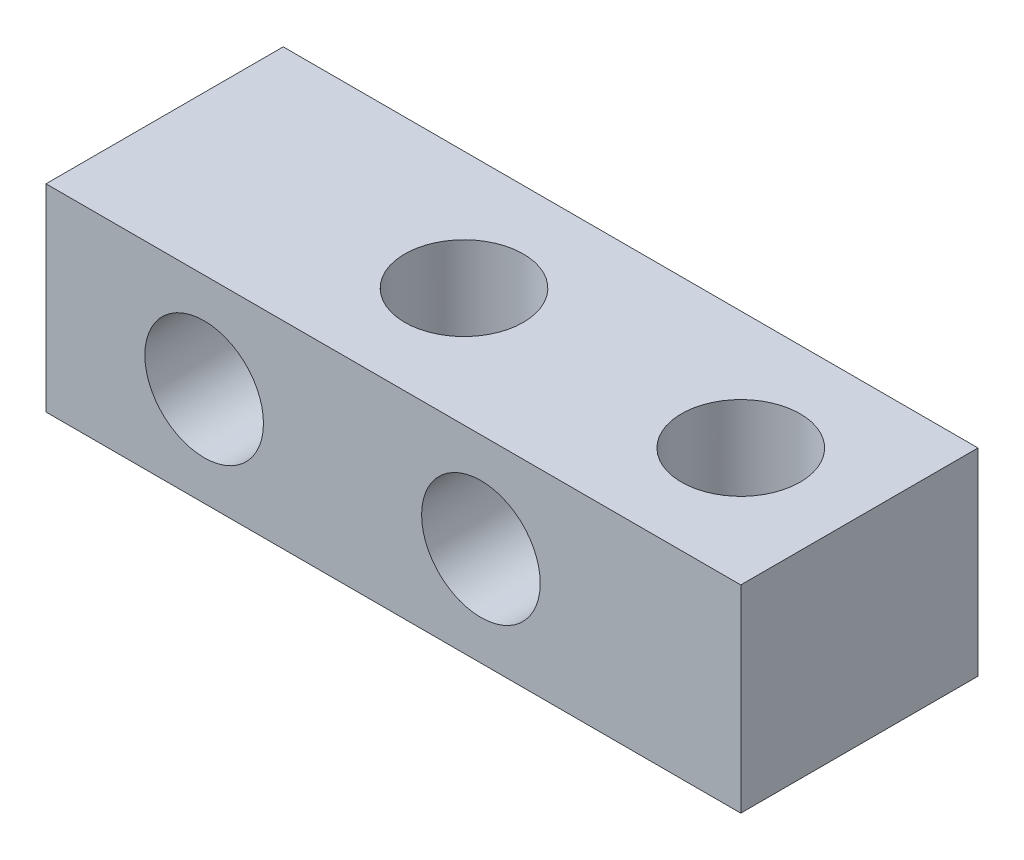
SolidWorks part; units mm, degrees
ref_plane "前视基准面" through (0, 0, 0) normal (0, 0, 1) x (1, 0, 0)
ref_plane "上视基准面" through (0, 0, 0) normal (0, 1, 0) x (1, 0, 0)
ref_plane "右视基准面" through (0, 0, 0) normal (1, 0, 0) x (0, 0, -1)
sketch "草图5" plane through (0, 0, 0) normal (0, 0, 1) x (1, 0, 0)
  line L0 (-30.9713, 4.45) -> (-30.9713, -0.55)
  line L1 (-64.4037, 4.45) -> (-32.2005, 4.45) construction
  line L2 (-30.9713, -16.55) -> (-30.9713, 4.45) construction
  line L3 (-30.9713, -0.55) -> (-48.5442, -0.55)
  line L4 (-48.5442, -16.55) -> (-48.5442, 4.45) construction
  line L5 (-48.5442, -0.55) -> (-48.5442, 4.45)
  line L6 (-48.5442, 4.45) -> (-30.9713, 4.45)
  dimension "D1" = 5
extrude "凸台-拉伸1" add sketch "草图5" along normal blind 6
sketch "草图6" plane through (0, 0, 6) normal (0, 0, 1) x (1, 0, 0)
  line L0 (-30.9713, 1.95) -> (-49.3316, 1.95) construction
  line L1 (-30.9713, -0.55) -> (-30.9713, 4.45) construction
  line L2 (-48.5442, -16.55) -> (-48.5442, 4.45) construction
  circle A0 centre (-37.5442, 1.95) radius 1.5
  circle A1 centre (-44.5442, 1.95) radius 1.5
  dimension "D1" = 3
  dimension "D2" = 3
  dimension "D4" = 4
  dimension "D3" = 7
extrude "切除-拉伸1" cut sketch "草图6" against normal through all both and the other way through all
sketch "草图7" plane through (0, -0.55, 0) normal (0, -1, 0) x (1, 0, 0)
  line L0 (-30.9713, 3) -> (-53.4905, 3) construction
  line L1 (-30.9713, 6) -> (-30.9713, 0) construction
  circle A0 centre (-40.9713, 3) radius 1.5
  circle A1 centre (-33.9713, 3) radius 1.5
  dimension "D1" = 3
  dimension "D2" = 3
  dimension "D3" = 7
  dimension "D4" = 3
extrude "切除-拉伸2" cut sketch "草图7" against normal through all both and the other way through all
